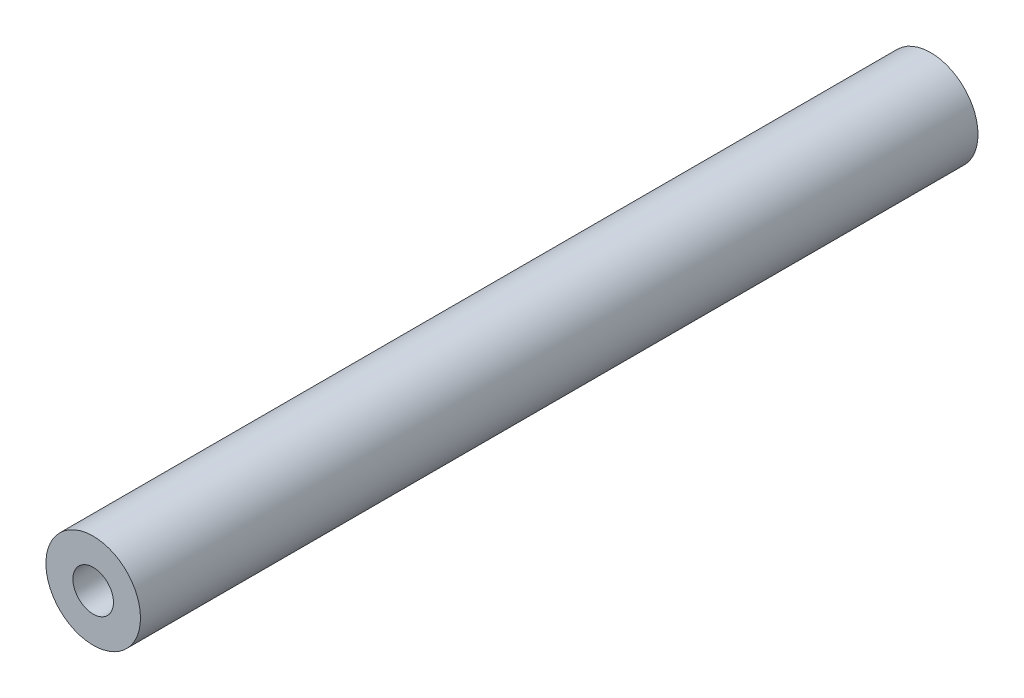
SolidWorks part; units mm, degrees
ref_plane "Front Plane" through (0, 0, 0) normal (0, 0, 1) x (1, 0, 0)
ref_plane "Top Plane" through (0, 0, 0) normal (0, 1, 0) x (1, 0, 0)
ref_plane "Right Plane" through (0, 0, 0) normal (1, 0, 0) x (0, 0, -1)
sketch "Sketch1" plane through (0, 0, 0) normal (0, 0, 1) x (1, 0, 0)
  circle A0 centre (0, 0) radius 1.5
  circle A1 centre (0, 0) radius 3.5
  dimension "D1" = 3
  dimension "D2" = 7
extrude "Boss-Extrude1" add sketch "Sketch1" along normal blind 62
